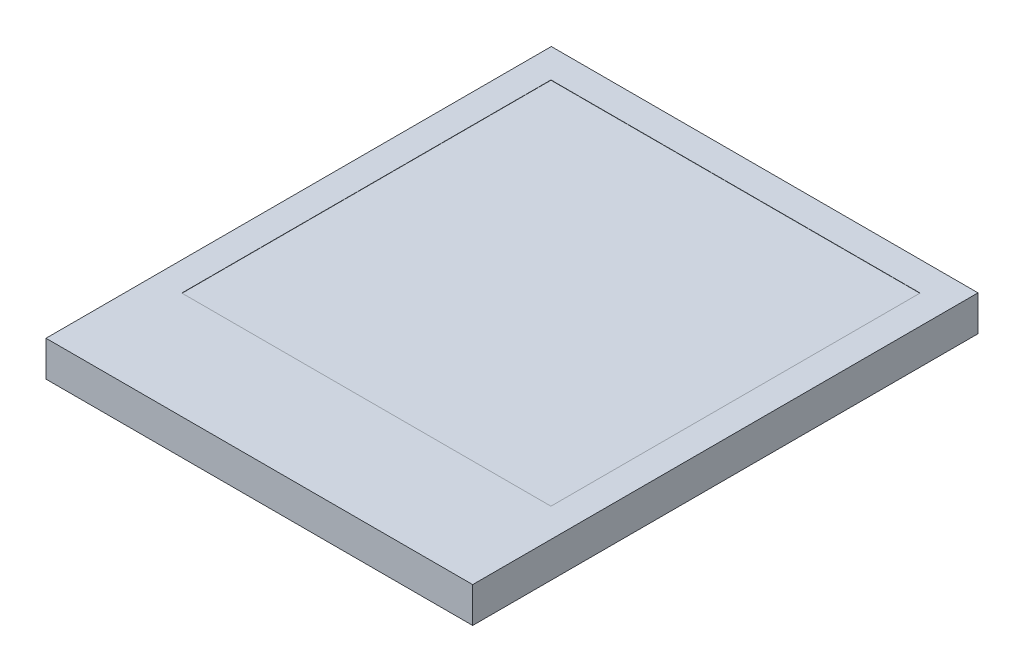
SolidWorks part; units mm, degrees
ref_plane "前视基准面" through (0, 0, 0) normal (0, 0, 1) x (1, 0, 0)
ref_plane "上视基准面" through (0, 0, 0) normal (0, 1, 0) x (1, 0, 0)
ref_plane "右视基准面" through (0, 0, 0) normal (1, 0, 0) x (0, 0, -1)
other "Configuration Table"
sketch "草图1" plane through (0, 0, 0) normal (0, 1, 0) x (1, 0, 0)
  line L1 (0, 0) -> (17.58, 0)
  line L2 (0, 0) -> (0, 20.82)
  line L3 (0, 20.82) -> (17.58, 20.82)
  line L4 (17.58, 0) -> (17.58, 20.82)
  line L5 (0, 0) -> (17.58, 20.82) construction
  line L6 (0, 20.82) -> (17.58, 0) construction
  point P4 (8.79, 10.41)
  dimension "D1" = 20.82
  dimension "D2" = 17.58
extrude "凸台-拉伸1" add sketch "草图1" along normal blind 1.46
sketch "草图2" plane through (0, 1.46, 0) normal (0, 1, 0) x (1, 0, 0)
  line L0 (8.79, 20.82) -> (8.79, 0) construction
  line L1 (1.185, 19.62) -> (16.395, 19.62)
  line L2 (1.185, 19.62) -> (1.185, 4.41)
  line L3 (1.185, 4.41) -> (16.395, 4.41)
  line L4 (16.395, 19.62) -> (16.395, 4.41)
  line L5 (1.185, 19.62) -> (16.395, 4.41) construction
  line L6 (1.185, 4.41) -> (16.395, 19.62) construction
  line L7 (17.58, 20.82) -> (0, 20.82) construction
  line L8 (0, 0) -> (17.58, 0) construction
  point P4 (8.79, 12.015)
  point P11 (8.79, 11.7863)
  dimension "D1" = 15.21
  dimension "D2" = 1.2
extrude "切除-拉伸1" cut sketch "草图2" against normal blind 0.01
